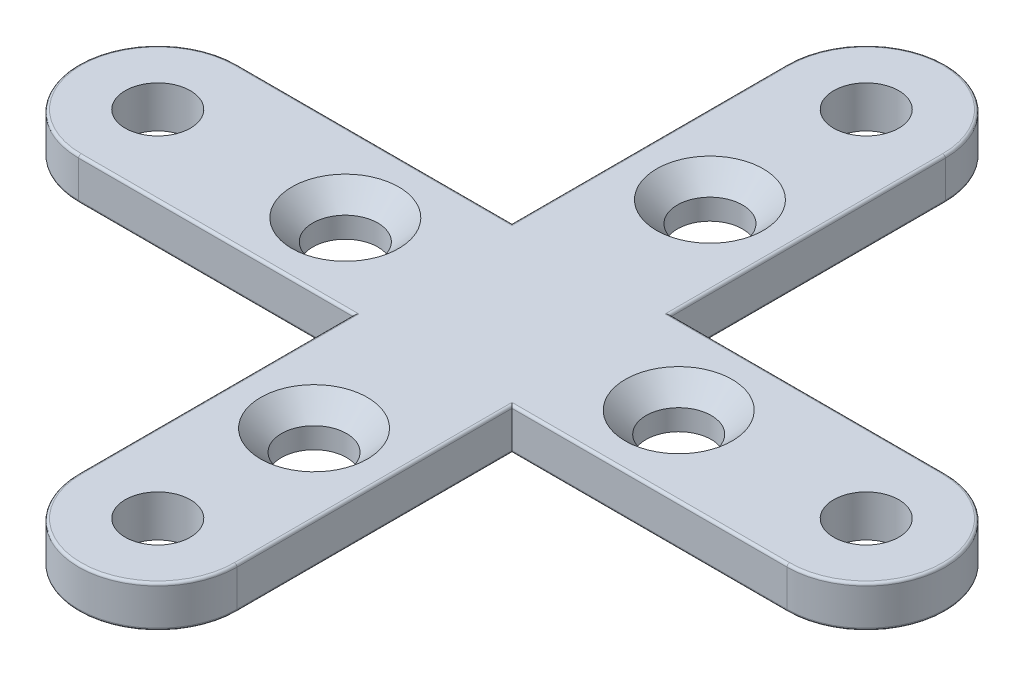
SolidWorks part; units mm, degrees
ref_plane "Front Plane" through (0, 0, 0) normal (0, 0, 1) x (1, 0, 0)
ref_plane "Top Plane" through (0, 0, 0) normal (0, 1, 0) x (1, 0, 0)
ref_plane "Right Plane" through (0, 0, 0) normal (1, 0, 0) x (0, 0, -1)
sketch "Sketch1" plane through (0, 0, 0) normal (0, 1, 0) x (1, 0, 0)
  line L0 (0, -17) -> (0, 17) construction
  line L1 (-3.8, -17) -> (-3.8, 17)
  line L2 (3.8, -17) -> (3.8, 17)
  line L3 (0, 0) -> (10.8491, 0) construction
  arc A0 (-3.8, -17) -> (3.8, -17) centre (0, -17) ccw
  arc A1 (3.8, 17) -> (-3.8, 17) centre (0, 17) ccw
  circle A2 centre (0, 17) radius 1.5625
  circle A3 centre (0, -17) radius 1.5625
  point P2 (0, 0)
  dimension "D4" = 3.125
  dimension "D3" = 34
  dimension "D1" = 7.6
  dimension "D2" = 34
extrude "Boss-Extrude1" add sketch "Sketch1" along normal blind 2
sketch3d "3DSketch1"
  line L0 (0, 0, 0) -> (0, 3, 0) construction
  dimension "D1" = 3
pattern_circular "CirPattern1" count 2 over 90 about axis through (0, 0, 0) along (0, 1, 0) of "Boss-Extrude1"
sketch "Sketch2" plane through (0, 0, 0) normal (0, 1, 0) x (1, 0, 0)
  line L0 (0, 0) -> (-1.9282, 0) construction
  line L1 (0, 0) -> (0, -2.0384) construction
  circle A0 centre (0, 9.5) radius 1.5625
  circle A1 centre (8, 0) radius 1.5625
  circle A2 centre (0, -9.5) radius 1.5625
  circle A3 centre (-8, 0) radius 1.5625
  dimension "D1" = 3.125
  dimension "D2" = 8
  dimension "D3" = 9.5
extrude "Cut-Extrude1" cut sketch "Sketch2" along normal up to surface (2 mm away) up to face at (0, 2, 0)
chamfer "Chamfer1" distance 1 angle 45 4 edges at (-8, 2, 1.5625) (0, 2, 11.0625) (8, 2, 1.5625) (0, 2, -7.9375)
fillet "Fillet1" radius 0.125 24 edges at (10.4, 2, 3.8) (20.8, 2, 0) (3.8, 2, 10.4) (0, 2, 20.8) (-10.4, 2, 3.8) (-20.8, 2, 0) (3.8, 2, -10.4) (0, 2, -20.8) (3.8, 0, -10.4) (0, 0, -20.8) (10.4, 0, -3.8) (20.8, 0, 0) (3.8, 0, 10.4) (0, 0, 20.8) (-10.4, 0, -3.8) (-10.4, 0, 3.8) (10.4, 2, -3.8) (-3.8, 2, 10.4) (-10.4, 2, -3.8) (-3.8, 2, -10.4) (-3.8, 0, -10.4) (10.4, 0, 3.8) (-3.8, 0, 10.4) (-20.8, 0, 0)
